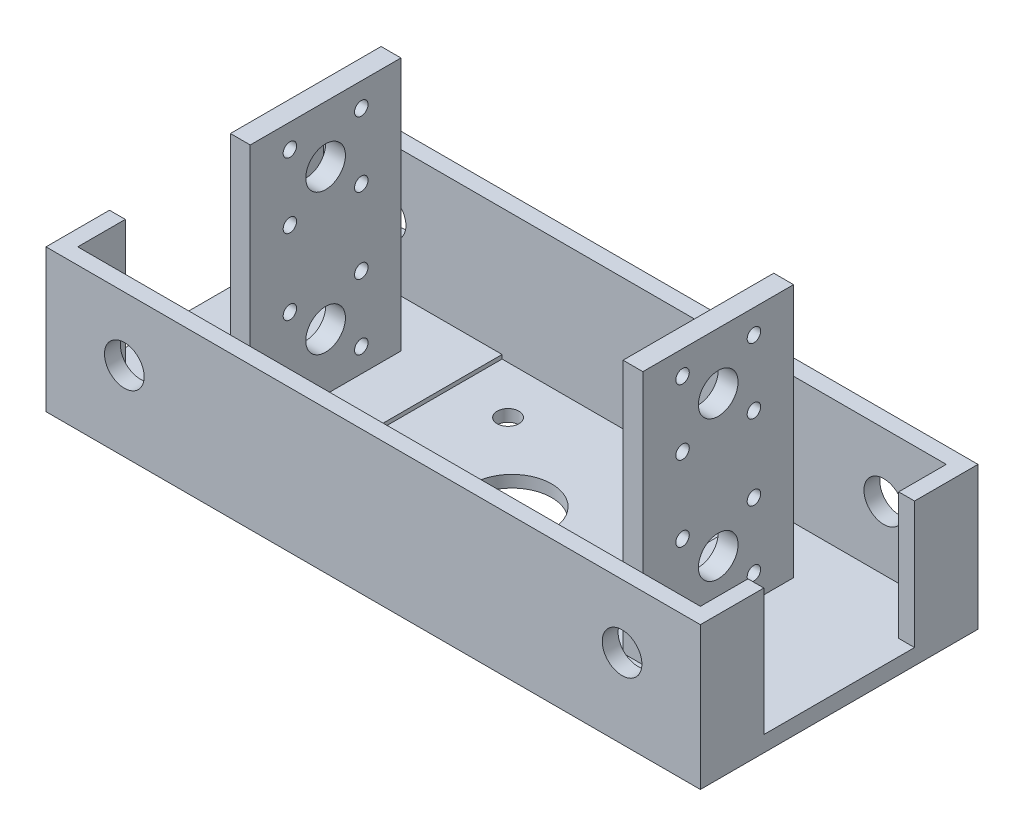
SolidWorks part; units mm, degrees
ref_plane "Front Plane" through (0, 0, 0) normal (0, 0, 1) x (1, 0, 0)
ref_plane "Top Plane" through (0, 0, 0) normal (0, 1, 0) x (1, 0, 0)
ref_plane "Right Plane" through (0, 0, 0) normal (1, 0, 0) x (0, 0, -1)
sketch "Sketch1" plane through (0, 0, 0) normal (0, 1, 0) x (1, 0, 0)
  line L0 (0, 0) -> (0, -14.43) construction
  line L1 (-37.5, 20) -> (37.5, 20)
  line L2 (-37.5, 20) -> (-37.5, -20)
  line L3 (-37.5, -20) -> (37.5, -20)
  line L4 (37.5, 20) -> (37.5, -20)
  line L5 (-37.5, 20) -> (37.5, -20) construction
  line L6 (-37.5, -20) -> (37.5, 20) construction
  line L7 (0, 0) -> (6.508, 0) construction
  line L8 (-5, 10) -> (5, 10)
  line L9 (-5, 10) -> (-5, -10)
  line L10 (-5, -10) -> (5, -10)
  line L11 (5, 10) -> (5, -10)
  line L12 (-5, 10) -> (5, -10) construction
  line L13 (-5, -10) -> (5, 10) construction
  circle A0 centre (-21, 0) radius 5
  circle A1 centre (-30, 8.25) radius 1.7
  circle A2 centre (-12, 8.25) radius 1.7
  circle A3 centre (-12, -8.25) radius 1.7
  circle A4 centre (-30, -8.25) radius 1.7
  circle A5 centre (12, 8.25) radius 1.7
  circle A6 centre (12, -8.25) radius 1.7
  circle A7 centre (21, 0) radius 5
  circle A8 centre (30, -8.25) radius 1.7
  circle A9 centre (30, 8.25) radius 1.7
  point P0 (0, 0)
  dimension "D3" = 10
  dimension "D4" = 16.5
  dimension "D5" = 16.5
  dimension "D6" = 18
  dimension "D9" = 10
  dimension "D11" = 20
  dimension "D13" = 7.5
  dimension "D17" = 3.4
  dimension "D19" = 11.75
  dimension "D20" = 11.75
  dimension "D1" = 75
  dimension "D2" = 40
  dimension "D10" = 10
  dimension "D7" = 2
  dimension "D8" = 2
extrude "Boss-Extrude1" add sketch "Sketch1" along normal blind 3
sketch "Sketch2" plane through (0, 3, 0) normal (0, 1, 0) x (1, 0, 0)
  line L0 (-37.5, 20) -> (-37.5, -20) construction
  line L1 (-33.5, 14) -> (33.5, 14)
  line L2 (-33.5, 14) -> (-33.5, -14)
  line L3 (-33.5, -14) -> (33.5, -14)
  line L4 (33.5, 14) -> (33.5, -14)
  line L5 (37.5, -20) -> (37.5, 20) construction
  line L6 (37.5, 20) -> (-37.5, 20) construction
  line L7 (-37.5, -20) -> (37.5, -20) construction
  dimension "D1" = 4
  dimension "D2" = 4
  dimension "D3" = 6
  dimension "D4" = 6
extrude "Cut-Extrude1" cut sketch "Sketch2" against normal through all both and the other way through all
sketch "Sketch3" plane through (0, 3, 0) normal (0, 1, 0) x (1, 0, 0)
  line L1 (37.5, 20) -> (-37.5, 20)
  line L2 (37.5, 20) -> (37.5, 35)
  line L3 (37.5, 35) -> (-37.5, 35)
  line L4 (-37.5, 20) -> (-37.5, 35)
  line L5 (-37.5, -20) -> (37.5, -20)
  line L6 (-37.5, -20) -> (-37.5, -35)
  line L7 (-37.5, -35) -> (37.5, -35)
  line L8 (37.5, -20) -> (37.5, -35)
  line L10 (-37.5, 20) -> (-33.5, 20)
  line L11 (-37.5, 20) -> (-37.5, -20)
  line L12 (-37.5, -20) -> (-33.5, -20)
  line L13 (-33.5, 20) -> (-33.5, -20)
  line L14 (37.5, 20) -> (33.5, 20)
  line L15 (37.5, 20) -> (37.5, -20)
  line L16 (37.5, -20) -> (33.5, -20)
  line L17 (33.5, 20) -> (33.5, -20)
  line M3 (-33.5, -14) -> (-33.5, 14)
  line M5 (33.5, 14) -> (33.5, -14)
  line M11 (37.5, -20) -> (37.5, 20)
  line M12 (37.5, 20) -> (-37.5, 20)
  line M13 (-37.5, 20) -> (-37.5, -20)
  line M14 (-37.5, -20) -> (37.5, -20)
  dimension "D1" = 15
  dimension "D2" = 15
extrude "Boss-Extrude3" add sketch "Sketch3" along normal blind 110 and the other way blind 3 contours L8 L5 L6 L7 M14 | L4 L1 L2 L3 M12 | L17 M12 M5 M14 M11 | L13 L1 M13 M14 M3
sketch "Sketch6" plane through (0, 3, 0) normal (0, 1, 0) x (1, 0, 0)
  line L0 (-37.5, -35) -> (37.5, -35) construction
  line L1 (-33.5, -20) -> (33.5, -20)
  line L2 (-33.5, -20) -> (-33.5, -31)
  line L3 (-33.5, -31) -> (33.5, -31)
  line L4 (33.5, -20) -> (33.5, -31)
  line L5 (33.5, 20) -> (-33.5, 20)
  line L6 (33.5, 20) -> (33.5, 31)
  line L7 (33.5, 31) -> (-33.5, 31)
  line L8 (-33.5, 20) -> (-33.5, 31)
  line L9 (37.5, 35) -> (-37.5, 35) construction
  dimension "D1" = 4
  dimension "D2" = 4
extrude "Cut-Extrude4" cut sketch "Sketch6" along normal through all
sketch "Sketch7" plane through (-37.5, 0, 0) normal (-1, 0, 0) x (0, 0, 1)
  line L0 (35, 0) -> (35, 113) construction
  line L1 (-35, 113) -> (35, 113)
  line L2 (-35, 113) -> (-35, 76)
  line L3 (-35, 76) -> (35, 76)
  line L4 (35, 113) -> (35, 76)
  dimension "D1" = 37
extrude "Boss-Extrude4" add sketch "Sketch7" along normal blind 45
ref_plane "Plane1" through (0, 0, 0) normal (1, 0, 0) x (0, 0, -1)
mirror "Mirror2" about plane through (0, 0, 0) normal (1, 0, 0) of "Boss-Extrude4"
sketch "Sketch8" plane through (0, 113, 0) normal (0, 1, 0) x (1, 0, 0)
  line L0 (-82.5, -35) -> (-82.5, 35) construction
  line L1 (-33.5, 31) -> (-78.5, 31)
  line L2 (-33.5, 31) -> (-33.5, -31)
  line L3 (-33.5, -31) -> (-78.5, -31)
  line L4 (-78.5, 31) -> (-78.5, -31)
  line L5 (33.5, -31) -> (78.5, -31)
  line L6 (33.5, -31) -> (33.5, 31)
  line L7 (33.5, 31) -> (78.5, 31)
  line L8 (78.5, -31) -> (78.5, 31)
  line L9 (82.5, -35) -> (82.5, 35) construction
  dimension "D1" = 4
  dimension "D2" = 4
extrude "Cut-Extrude6" cut sketch "Sketch8" against normal blind 29
sketch "Sketch9" plane through (-82.5, 0, 0) normal (-1, 0, 0) x (0, 0, 1)
  line L18 (-31, 84) -> (31, 84) construction
  line L19 (-19, 84) -> (19, 84)
  line L20 (-19, 84) -> (-19, 112.5)
  line L21 (-19, 112.5) -> (19, 112.5)
  line L22 (19, 84) -> (19, 112.5)
  line L25 (-31, 84) -> (-31, 113) construction
  dimension "D1" = 38
  dimension "D2" = 12
  dimension "D3" = 28.5
sketch "Sketch11" plane through (0, 0, 35) normal (0, 0, 1) x (1, 0, 0)
  line L0 (82.5, 76) -> (82.5, 113) construction
  line L1 (-82.5, 76) -> (-37.5, 76)
  line L2 (-82.5, 76) -> (-82.5, 80)
  line L3 (-82.5, 80) -> (-37.5, 80)
  line L4 (-37.5, 76) -> (-37.5, 80)
  line L5 (37.5, 76) -> (82.5, 76)
  line L6 (37.5, 76) -> (37.5, 80)
  line L7 (37.5, 80) -> (82.5, 80)
  line L8 (82.5, 76) -> (82.5, 80)
  line L11 (-78.5, 84) -> (-33.5, 84) construction
  line L12 (33.5, 84) -> (78.5, 84) construction
  dimension "D1" = 4
  dimension "D2" = 4
extrude "Cut-Extrude9" cut sketch "Sketch11" against normal through all
extrude "Cut-Extrude10" cut sketch "Sketch9" against normal through all
sketch "Sketch13" plane through (0, 84, 0) normal (0, 1, 0) x (1, 0, 0)
  line L0 (-78.5, 31) -> (-78.5, -31) construction
  line L1 (-52, 19) -> (-47, 19)
  line L2 (-52, 19) -> (-52, -19)
  line L3 (-52, -19) -> (-47, -19)
  line L4 (-47, 19) -> (-47, -19)
  line L7 (78.5, 31) -> (-78.5, 31) construction
  line L13 (-52, -19) -> (-52, 19)
  line L17 (-82.5, -19) -> (-107.5, -19)
  line L18 (-82.5, -19) -> (-82.5, 19)
  line L19 (-82.5, 19) -> (-107.5, 19)
  line L20 (-107.5, -19) -> (-107.5, 19)
  line L21 (-107.5, 19) -> (-61, 19)
  line L22 (-107.5, 19) -> (-107.5, -19)
  line L23 (-107.5, -19) -> (-61, -19)
  line L24 (-61, 19) -> (-61, -19)
  dimension "D1" = 26.5
  dimension "D2" = 5
  dimension "D3" = 38
  dimension "D4" = 12
  dimension "D5" = 25
  dimension "D6" = 46.5
extrude "Boss-Extrude5" add sketch "Sketch13" along normal blind 32 contours L4 L1 L2 L3
sketch "Sketch14" plane through (-52, 0, 0) normal (-1, 0, 0) x (0, 0, 1)
  line L0 (-19, 116) -> (-19, 84) construction
  line L4 (19, 112.5) -> (-19, 112.5) construction
  circle A0 centre (0, 98.25) radius 5
  circle A1 centre (-9, 106.5) radius 1.7
  circle A2 centre (9, 106.5) radius 1.7
  circle A3 centre (9, 90) radius 1.7
  circle A4 centre (-9, 90) radius 1.7
  dimension "D1" = 19
  dimension "D2" = 9
  dimension "D3" = 10
  dimension "D6" = 3.4
  dimension "D7" = 14.25
  dimension "D8" = 16.5
  dimension "D9" = 18
  dimension "D10" = 8.25
  dimension "D4" = 2
  dimension "D5" = 2
extrude "Cut-Extrude11" cut sketch "Sketch14" against normal blind 32
mirror "Mirror4" about plane through (0, 0, 0) normal (1, 0, 0) of "Boss-Extrude5", "Cut-Extrude11"
sketch "Sketch15" plane through (0, 113, 0) normal (0, 1, 0) x (1, 0, 0)
  line L1 (-82.5, 35) -> (82.5, 35)
  line L2 (-82.5, 35) -> (-82.5, -35)
  line L3 (-82.5, -35) -> (82.5, -35)
  line L4 (82.5, 35) -> (82.5, -35)
  line L5 (-78.5, 31) -> (78.5, 31)
  line L6 (-78.5, 31) -> (-78.5, -31)
  line L7 (-78.5, -31) -> (78.5, -31)
  line L8 (78.5, 31) -> (78.5, -31)
extrude "Boss-Extrude6" add sketch "Sketch15" along normal blind 3
sketch "Sketch16" plane through (0, 0, 35) normal (0, 0, 1) x (1, 0, 0)
  line L1 (-10, 14.0464) -> (10, 14.0464)
  line L2 (-10, 14.0464) -> (-10, 9.2258)
  line L3 (-10, 9.2258) -> (10, 9.2258)
  line L4 (10, 14.0464) -> (10, 9.2258)
  line L5 (-37.5, 0) -> (-37.5, 80) construction
  dimension "D1" = 20
  dimension "D2" = 27.5
extrude "Cut-Extrude12" cut sketch "Sketch16" against normal through all
sketch "Sketch18" plane through (0, 0, 35) normal (0, 0, 1) x (1, 0, 0)
  line L0 (52, 116) -> (52, 84) construction
  line L2 (33.5, 84) -> (78.5, 84) construction
  circle A0 centre (62.75, 100) radius 5
  dimension "D1" = 10.75
  dimension "D2" = 16
  dimension "D3" = 10
extrude "Cut-Extrude14" cut sketch "Sketch18" against normal through all
mirror "Mirror5" about plane through (0, 0, 0) normal (1, 0, 0) of "Cut-Extrude14"
mirror "Mirror6" about plane through (0, 116, 0) normal (0, 1, 0) of "Mirror4", "Boss-Extrude5", "Cut-Extrude11"
sketch "Sketch19" plane through (82.5, 0, 0) normal (1, 0, 0) x (0, 0, -1)
  line L0 (19, 148) -> (19, 84) construction
  line L1 (-19, 112.5) -> (19, 112.5)
  line L2 (-19, 112.5) -> (-19, 116)
  line L3 (-19, 116) -> (19, 116)
  line L4 (19, 112.5) -> (19, 116)
extrude "Cut-Extrude15" cut sketch "Sketch19" against normal blind 10
mirror "Mirror7" about plane through (0, 0, 0) normal (1, 0, 0) of "Cut-Extrude15"
sketch "Sketch20" plane through (0, 3, 0) normal (0, 1, 0) x (1, 0, 0)
  line L0 (33.5, 31) -> (-33.5, 31) construction
  line L1 (-5, -10) -> (5, -10)
  line L2 (-5, -10) -> (-5, 10)
  line L3 (-5, 10) -> (5, 10)
  line L4 (5, -10) -> (5, 10)
  line L5 (-5, -10) -> (5, 10) construction
  line L6 (-5, 10) -> (5, -10) construction
  line L7 (0, 0) -> (0, 17.5) construction
  line L8 (-37.5, 20) -> (37.5, 20)
  line L9 (-37.5, 20) -> (-37.5, -20)
  line L10 (-37.5, -20) -> (37.5, -20)
  line L11 (37.5, 20) -> (37.5, -20)
  line L12 (-37.5, 20) -> (37.5, -20) construction
  line L13 (-37.5, -20) -> (37.5, 20) construction
  line L14 (0, -34.1) -> (0, 34.1) construction
  circle A1 centre (-12, 17.5) radius 1.2
  circle A2 centre (-12, -17.5) radius 1.2
  circle A3 centre (-24, -17.5) radius 1.2
  circle A4 centre (-24, 17.5) radius 1.2
  circle A5 centre (12, -17.5) radius 1.2
  circle A6 centre (24, -17.5) radius 1.2
  circle A7 centre (12, 17.5) radius 1.2
  circle A8 centre (24, 17.5) radius 1.2
  point P2 (0, 0)
  point P10 (0, 0)
  dimension "D1" = 7
  dimension "D2" = 10
  dimension "D4" = 2.5
  dimension "D7" = 35
  dimension "D8" = 7
  dimension "D9" = 2.4
  dimension "D11" = 12
  dimension "D3" = 21
  dimension "D5" = 75
  dimension "D6" = 40
  dimension "D10" = 2
extrude "Cut-Extrude16" cut sketch "Sketch20" against normal blind 10 contours A4 | A1 | A7 | A3 | A2 | A8 | A5 | A6
sketch "Sketch21" plane through (0, 0, 35) normal (0, 0, 1) x (1, 0, 0)
  line L0 (0, -34.1) -> (0, 34.1) construction
  line L1 (37.5, 0) -> (27.5, 0)
  line L2 (37.5, 0) -> (37.5, 80)
  line L3 (37.5, 80) -> (27.5, 80)
  line L4 (27.5, 0) -> (27.5, 80)
  line L5 (-27.5, 0) -> (-27.5, 80)
  line L6 (-37.5, 80) -> (-27.5, 80)
  line L7 (-37.5, 0) -> (-37.5, 80)
  line L8 (-37.5, 0) -> (-27.5, 0)
  dimension "D1" = 10
  dimension "D2" = 80
extrude "Cut-Extrude17" cut sketch "Sketch21" against normal through all
sketch "Sketch22" plane through (0, 0, 35) normal (0, 0, 1) x (1, 0, 0)
  line L1 (-27.5, 0) -> (27.5, 0)
  line L2 (-27.5, 0) -> (-27.5, 80)
  line L3 (-27.5, 80) -> (27.5, 80)
  line L4 (27.5, 0) -> (27.5, 80)
extrude "Cut-Extrude18" cut sketch "Sketch22" against normal through all
sketch "Sketch23" plane through (0, 80, 0) normal (0, -1, 0) x (1, 0, 0)
  line L1 (-33.5, 31) -> (33.5, 31)
  line L2 (-33.5, 31) -> (-33.5, -31)
  line L3 (-33.5, -31) -> (33.5, -31)
  line L4 (33.5, 31) -> (33.5, -31)
extrude "Boss-Extrude7" add sketch "Sketch23" against normal blind 3
sketch "Sketch24" plane through (0, 83, 0) normal (0, 1, 0) x (1, 0, 0)
  line L5 (78.5, 31) -> (-78.5, 31) construction
  line L9 (33.5, -31) -> (-33.5, -31) construction
  line L10 (0, 0) -> (0, 16.8876) construction
  line L11 (0, -34.1) -> (0, 34.1) construction
  circle A0 centre (0, 0) radius 10
  circle A1 centre (-20, 19) radius 2.75
  circle A2 centre (-20, -19) radius 2.75
  circle A3 centre (20, -19) radius 2.75
  circle A4 centre (20, 19) radius 2.75
  dimension "D1" = 20
  dimension "D2" = 12
  dimension "D3" = 20
  dimension "D4" = 12
extrude "Cut-Extrude19" cut sketch "Sketch24" against normal through all
